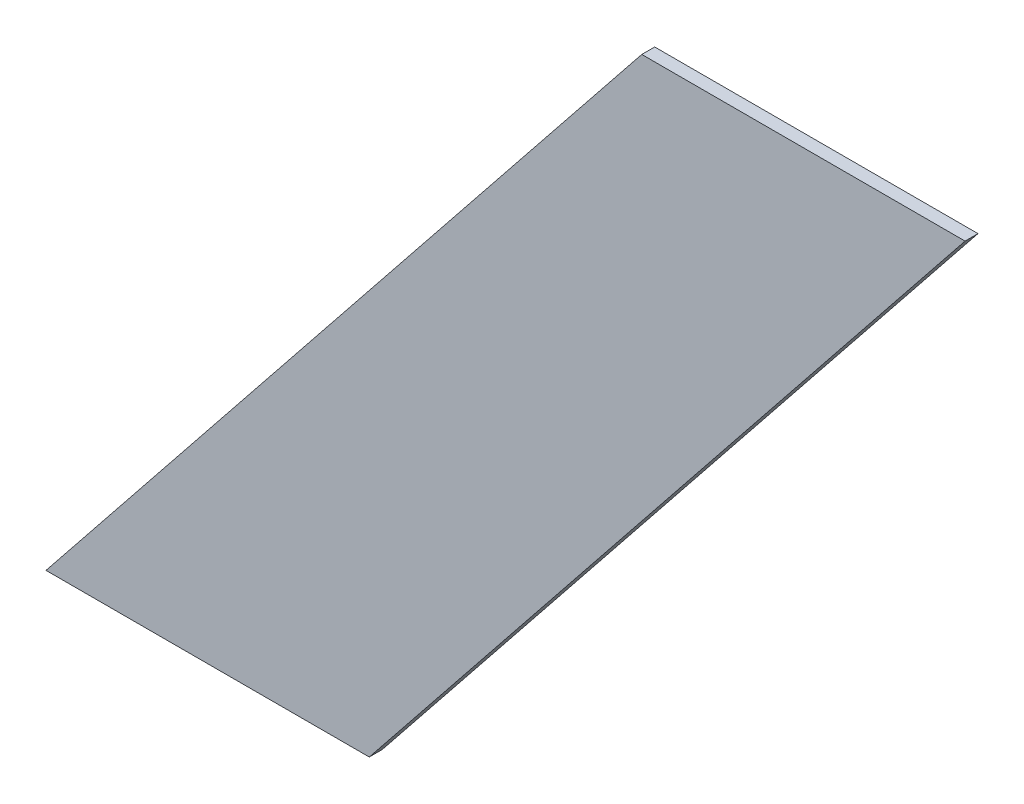
SolidWorks part; units mm, degrees
ref_plane "Front Plane" through (0, 0, 0) normal (0, 0, 1) x (1, 0, 0)
ref_plane "Top Plane" through (0, 0, 0) normal (0, 1, 0) x (1, 0, 0)
ref_plane "Right Plane" through (0, 0, 0) normal (1, 0, 0) x (0, 0, -1)
sketch "Sketch2" plane through (0, 0, 0) normal (0, 0, 1) x (1, 0, 0)
  line L0 (0, 0) -> (93.6172, 117.0207)
  line L1 (93.6172, 117.0207) -> (144.4172, 117.0207)
  line L2 (144.4172, 117.0207) -> (50.8, 0)
  line L3 (50.8, 0) -> (0, 0)
  dimension "D1" = 51.34
  dimension "D2" = 149.86
  dimension "D3" = 50.8
extrude "Boss-Extrude1" add sketch "Sketch2" along normal blind 2.032
